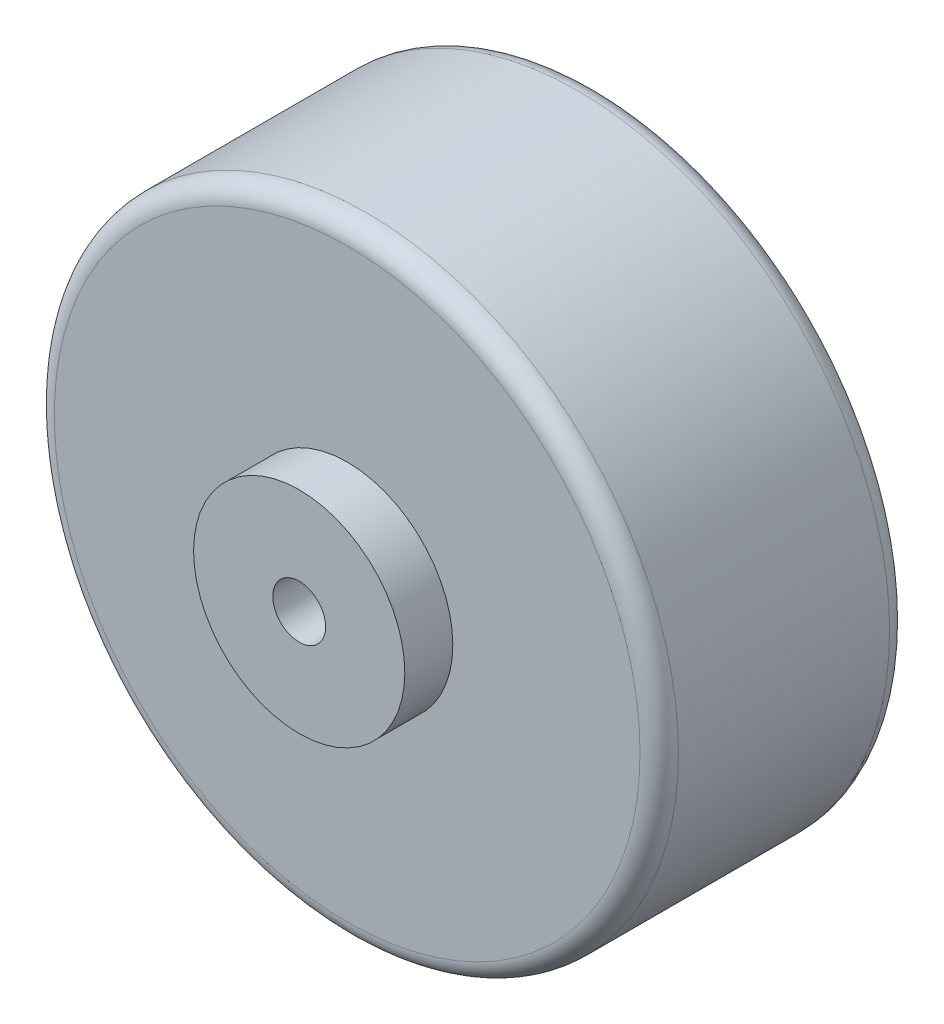
SolidWorks part; units mm, degrees
ref_plane "Front Plane" through (0, 0, 0) normal (0, 0, 1) x (1, 0, 0)
ref_plane "Top Plane" through (0, 0, 0) normal (0, 1, 0) x (1, 0, 0)
ref_plane "Right Plane" through (0, 0, 0) normal (1, 0, 0) x (0, 0, -1)
sketch "Sketch1" plane through (0, 0, 0) normal (0, 0, 1) x (1, 0, 0)
  circle A0 centre (0, 0) radius 32.5
  dimension "D1" = 65
extrude "Boss-Extrude1" add sketch "Sketch1" along normal blind 26
sketch "Sketch2" plane through (0, 0, 26) normal (0, 0, 1) x (1, 0, 0)
  circle A0 centre (0, 0) radius 11
  dimension "D1" = 22
extrude "Boss-Extrude2" add sketch "Sketch2" along normal blind 5
sketch "Sketch3" plane through (0, 0, 31) normal (0, 0, 1) x (1, 0, 0)
  circle A0 centre (0, 0) radius 2.75
  dimension "D1" = 5.5
extrude "Cut-Extrude1" cut sketch "Sketch3" against normal through all
fillet "Fillet1" radius 2 2 edges at (32.5, 0, 0) (32.5, 0, 26)
